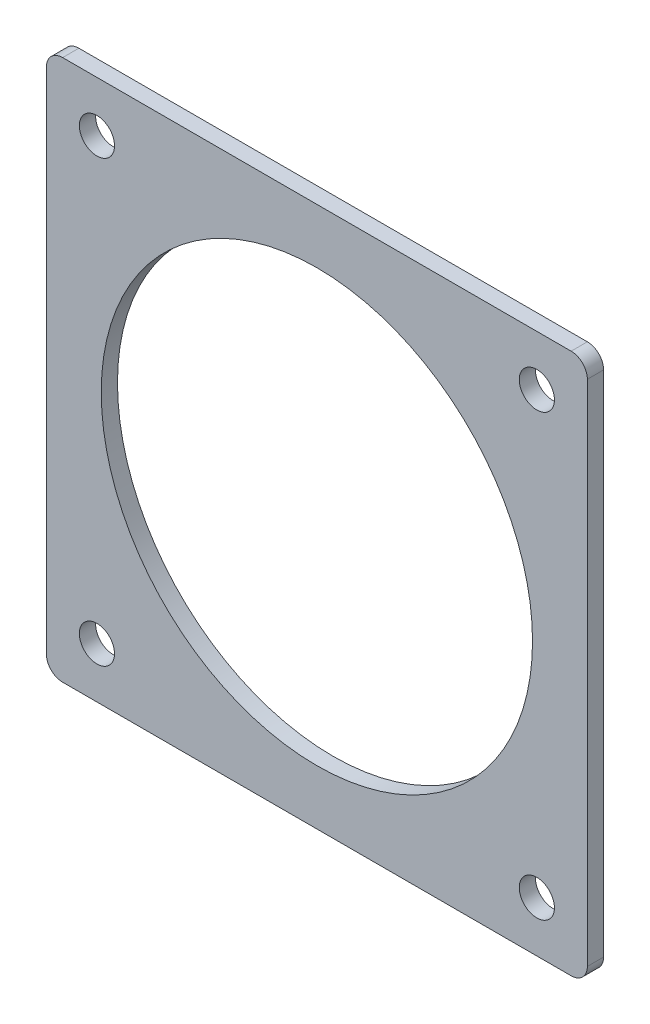
SolidWorks part; units mm, degrees
ref_plane "Front Plane" through (0, 0, 0) normal (0, 0, 1) x (1, 0, 0)
ref_plane "Top Plane" through (0, 0, 0) normal (0, 1, 0) x (1, 0, 0)
ref_plane "Right Plane" through (0, 0, 0) normal (1, 0, 0) x (0, 0, -1)
sketch "Sketch1" plane through (0, 0, 0) normal (0, 0, 1) x (1, 0, 0)
  line L1 (-47, 50) -> (47, 50)
  line L2 (-50, 47) -> (-50, -47)
  line L3 (-47, -50) -> (47, -50)
  line L4 (50, 47) -> (50, -47)
  line L5 (-50, 50) -> (50, -50) construction
  line L6 (-50, -50) -> (50, 50) construction
  circle A0 centre (0, 0) radius 39.8627
  arc A1 (28.3945, 50) -> (-28.3945, 50) centre (0, 0) ccw construction
  arc A2 (-40.6586, 40.6586) -> (-50, -28.3945) centre (0, 0) ccw construction
  arc A3 (50, -28.3945) -> (40.6586, 40.6586) centre (0, 0) ccw construction
  arc A4 (-40.6586, -40.6586) -> (40.6586, -40.6586) centre (0, 0) ccw construction
  circle A5 centre (40.6586, 40.6586) radius 3.25
  circle A6 centre (-40.6586, 40.6586) radius 3.25
  circle A7 centre (-40.6586, -40.6586) radius 3.25
  circle A8 centre (40.6586, -40.6586) radius 3.25
  arc A9 (47, 50) -> (50, 47) centre (47, 47) cw
  arc A10 (47, -50) -> (50, -47) centre (47, -47) ccw
  arc A11 (-50, -47) -> (-47, -50) centre (-47, -47) ccw
  arc A12 (-47, 50) -> (-50, 47) centre (-47, 47) ccw
  dimension "D3" = 115
  dimension "D4" = 6.5
  dimension "D5" = 3
  dimension "D1" = 100
  dimension "D2" = 100
extrude "Boss-Extrude1" add sketch "Sketch1" along normal blind 3
